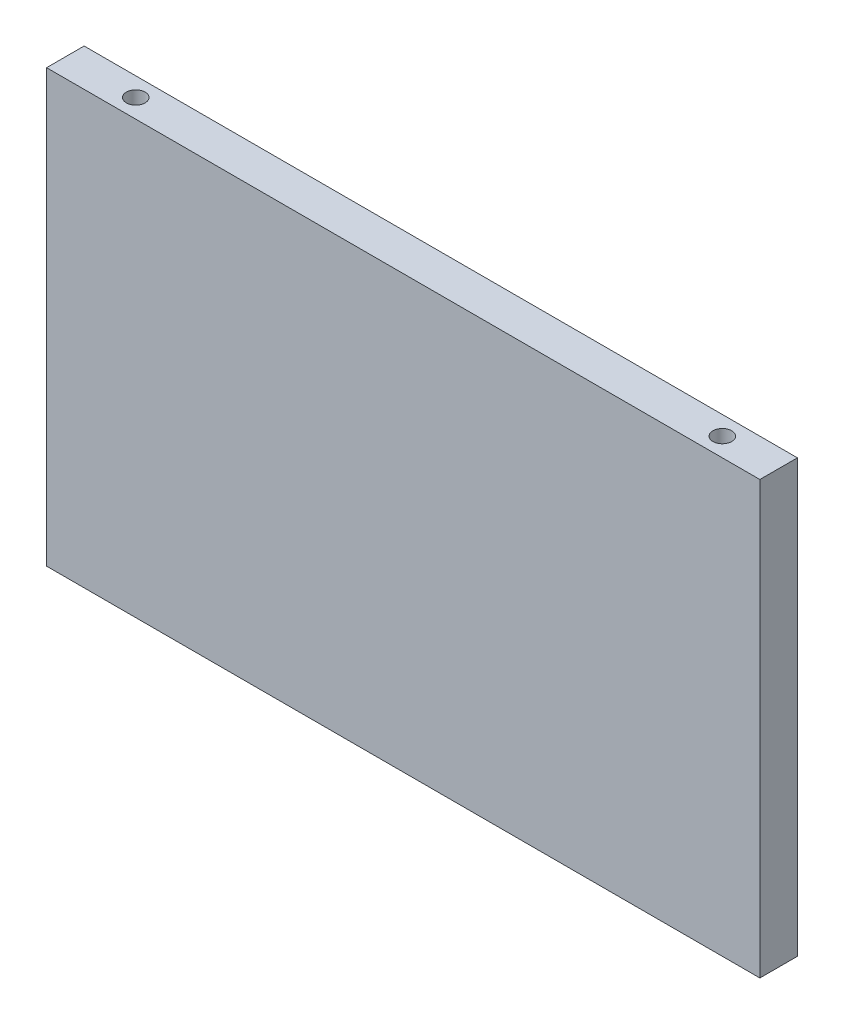
SolidWorks part; units mm, degrees
ref_plane "Plan de face" through (0, 0, 0) normal (0, 0, 1) x (1, 0, 0)
ref_plane "Plan de dessus" through (0, 0, 0) normal (0, 1, 0) x (1, 0, 0)
ref_plane "Plan de droite" through (0, 0, 0) normal (1, 0, 0) x (0, 0, -1)
sketch "Esquisse1" plane through (0, 0, 0) normal (0, 0, 1) x (1, 0, 0)
  line L1 (76, -46) -> (-76, -46)
  line L2 (76, -46) -> (76, 46)
  line L3 (76, 46) -> (-76, 46)
  line L4 (-76, -46) -> (-76, 46)
  line L5 (76, -46) -> (-76, 46) construction
  line L6 (76, 46) -> (-76, -46) construction
  point P0 (0, 0)
  dimension "D1" = 152
  dimension "D2" = 92
extrude "Boss.-Extru.1" add sketch "Esquisse1" along normal blind 8
sketch "Esquisse2" plane through (0, -46, 0) normal (0, -1, 0) x (1, 0, 0)
  line L0 (-76, 8) -> (-76, 0) construction
  line L1 (-76, 0) -> (76, 0) construction
  circle A0 centre (64, 4) radius 2
  circle A1 centre (-61, 4) radius 2
  point P6 (0, 0)
  point P9 (-60.5, 4)
  dimension "D1" = 125
  dimension "D4" = 4
  dimension "D5" = 4
  dimension "D2" = 15
  dimension "D3" = 4
extrude "Enlèv. mat.-Extru.1" cut sketch "Esquisse2" against normal through all
